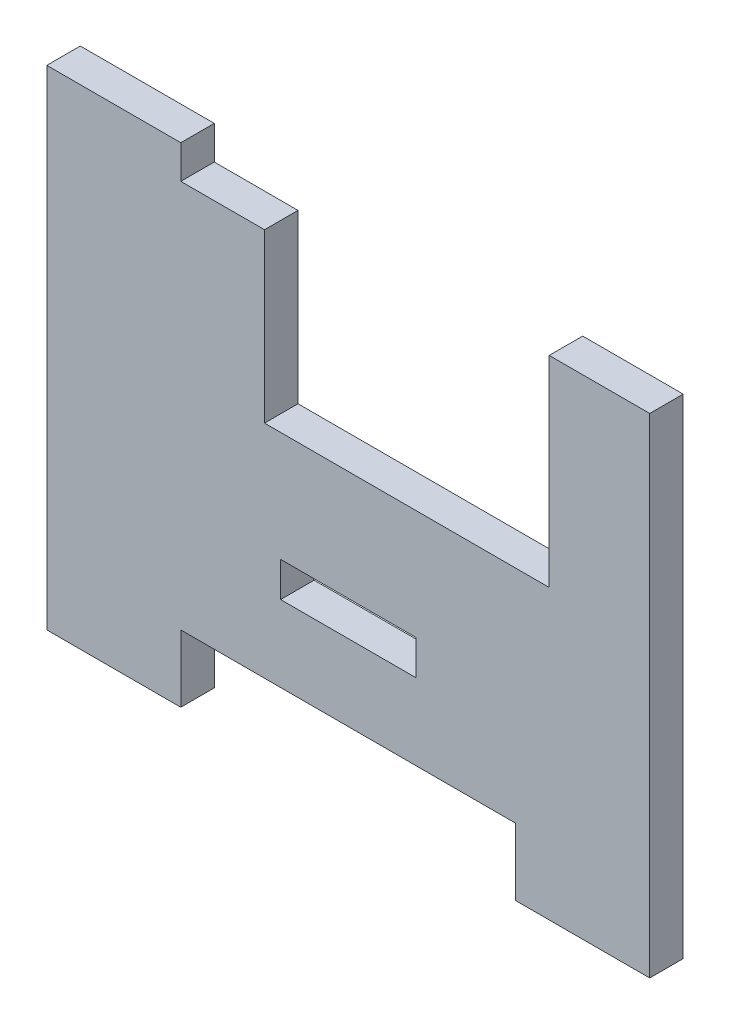
SolidWorks part; units mm, degrees
ref_plane "Front Plane" through (0, 0, 0) normal (0, 0, 1) x (1, 0, 0)
ref_plane "Top Plane" through (0, 0, 0) normal (0, 1, 0) x (1, 0, 0)
ref_plane "Right Plane" through (0, 0, 0) normal (1, 0, 0) x (0, 0, -1)
sketch "Sketch2" plane through (0, 0, 0) normal (0, 0, -1) x (1, 0, 0)
  line L0 (-139.7, 73.64) -> (-139.7, 0) construction
  line L1 (0, 0) -> (-279.4, 0) construction
  line L2 (0, 0) -> (0, 73.64) construction
  line L3 (0, 73.64) -> (-82.55, 73.64)
  line L4 (-279.4, 0) -> (-279.4, 73.64) construction
  line L5 (-82.55, 73.64) -> (-82.55, 0)
  line L6 (-196.85, 73.64) -> (-196.85, 0)
  line L7 (-101.6, 0) -> (-101.6, 31.75)
  line L8 (-101.6, 31.75) -> (-155.575, 31.75)
  line L9 (-155.575, 31.75) -> (-155.575, 0)
  line L10 (-171.45, 73.64) -> (-171.45, 86.34)
  line L12 (-82.55, 73.64) -> (-82.55, 86.34)
  line L13 (-82.55, 86.34) -> (-107.95, 86.34)
  line L14 (-107.95, 73.64) -> (-107.95, 86.34)
  line L15 (-196.85, 86.34) -> (-171.45, 86.34)
  line L16 (-196.85, 73.64) -> (-196.85, 86.34)
  line L18 (-107.95, 73.64) -> (-171.45, 73.64)
  line L19 (-196.85, 73.64) -> (-279.4, 73.64) construction
  line L20 (-155.575, 0) -> (-171.45, 0)
  line L21 (-82.55, 0) -> (-101.6, 0) construction
  line L22 (-82.55, 0) -> (-82.55, -6.35)
  line L23 (-82.55, -6.35) -> (-101.6, -6.35)
  line L24 (-101.6, 0) -> (-101.6, -6.35)
  line L25 (-196.85, 0) -> (-171.45, 0) construction
  line L26 (-196.85, 0) -> (-196.85, -6.35)
  line L27 (-196.85, -6.35) -> (-171.45, -6.35)
  line L28 (-171.45, 0) -> (-171.45, -6.35)
  line L37 (-126.873, 59.197) -> (-152.527, 59.197)
  line L38 (-152.527, 59.197) -> (-152.527, 52.593)
  line L39 (-152.527, 52.593) -> (-126.873, 52.593)
  line L40 (-126.873, 52.593) -> (-126.873, 59.197)
  line L41 (-126.873, 59.197) -> (-152.527, 59.197)
  line L42 (-152.527, 59.197) -> (-152.527, 52.593)
  line L43 (-152.527, 52.593) -> (-126.873, 52.593)
  line L44 (-126.873, 52.593) -> (-126.873, 59.197)
  dimension "D1" = 279.4
  dimension "D2" = 73.64
  dimension "D3" = 114.3
  dimension "D4" = 19.05
  dimension "D5" = 31.75
  dimension "D6" = 53.975
  dimension "D7" = 25.4
  dimension "D8" = 12.7
  dimension "D9" = 6.35
  dimension "D10" = 6.35
  dimension "D11" = 25.4
  dimension "D12" = 0.127
extrude "Boss-Extrude1" add sketch "Sketch2" along normal blind 6.35 contours L20 L28 L27 L26 L6 L16 L15 L10 L18 L14 L13 L12 L5 L22 L23 L24 L7 L8 L9
